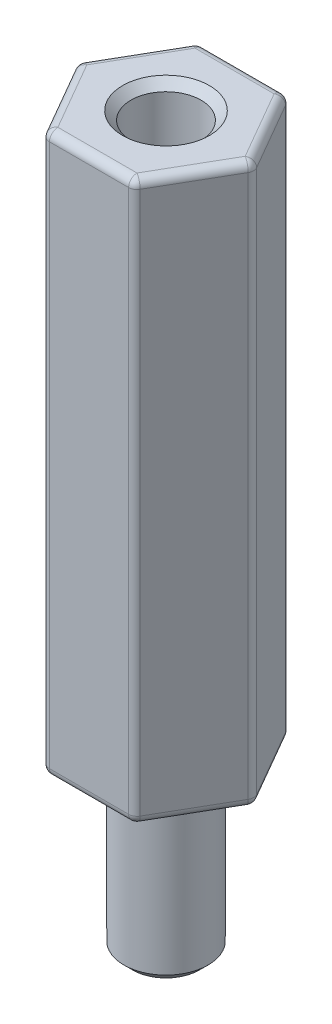
SolidWorks part; units mm, degrees
material "Cast Stainless Steel"
ref_plane "Front Plane" through (0, 0, 0) normal (0, 0, 1) x (1, 0, 0)
ref_plane "Top Plane" through (0, 0, 0) normal (0, 1, 0) x (1, 0, 0)
ref_plane "Right Plane" through (0, 0, 0) normal (1, 0, 0) x (0, 0, -1)
sketch "Sketch1" plane through (0, 0, 0) normal (0, 1, 0) x (1, 0, 0)
  line L1 (-1.5877, 2.75) -> (-3.1754, 0)
  line L2 (-3.1754, 0) -> (-1.5877, -2.75)
  line L3 (-1.5877, -2.75) -> (1.5877, -2.75)
  line L4 (1.5877, -2.75) -> (3.1754, 0)
  line L5 (3.1754, 0) -> (1.5877, 2.75)
  line L6 (1.5877, 2.75) -> (-1.5877, 2.75)
  circle A0 centre (0, 0) radius 2.75 construction
  circle A1 centre (0, 0) radius 1.25
  dimension "D2" = 2.5
  dimension "D1" = 5.5
extrude "Boss-Extrude1" add sketch "Sketch1" along normal blind 20
fillet "Fillet1" radius 0.3 6 edges at (1.5877, 10, -2.75) (3.1754, 10, 0) (-1.5877, 10, -2.75) (-3.1754, 10, 0) (-1.5877, 10, 2.75) (1.5877, 10, 2.75)
fillet "Fillet2" radius 0.3 24 edges at (-1.5645, 0, 2.7098) (-2.3816, 0, 1.375) (-3.129, 0, 0) (-2.3816, 0, -1.375) (-1.5645, 0, -2.7098) (0, 0, -2.75) (1.5645, 0, -2.7098) (2.3816, 0, -1.375) (3.129, 0, 0) (2.3816, 0, 1.375) (1.5645, 0, 2.7098) (-1.5645, 20, 2.7098) (-2.3816, 20, 1.375) (-3.129, 20, 0) (-2.3816, 20, -1.375) (-1.5645, 20, -2.7098) (0, 20, -2.75) (1.5645, 20, -2.7098) (2.3816, 20, -1.375) (3.129, 20, 0) (2.3816, 20, 1.375) (1.5645, 20, 2.7098) (0, 0, 2.75) (0, 20, 2.75)
sketch "Sketch2" plane through (0, 0, 0) normal (0, -1, 0) x (1, 0, 0)
  circle A0 centre (0, 0) radius 1.5
  dimension "D1" = 3
extrude "Boss-Extrude2" add sketch "Sketch2" along normal blind 6
chamfer "Chamfer1" distance 0.3 angle 45 2 edges at (0, 20, 1.25) (0, -6, -1.5)
fillet "Fillet3" radius 0.3 1 edges at (0, 0, 1.5)
